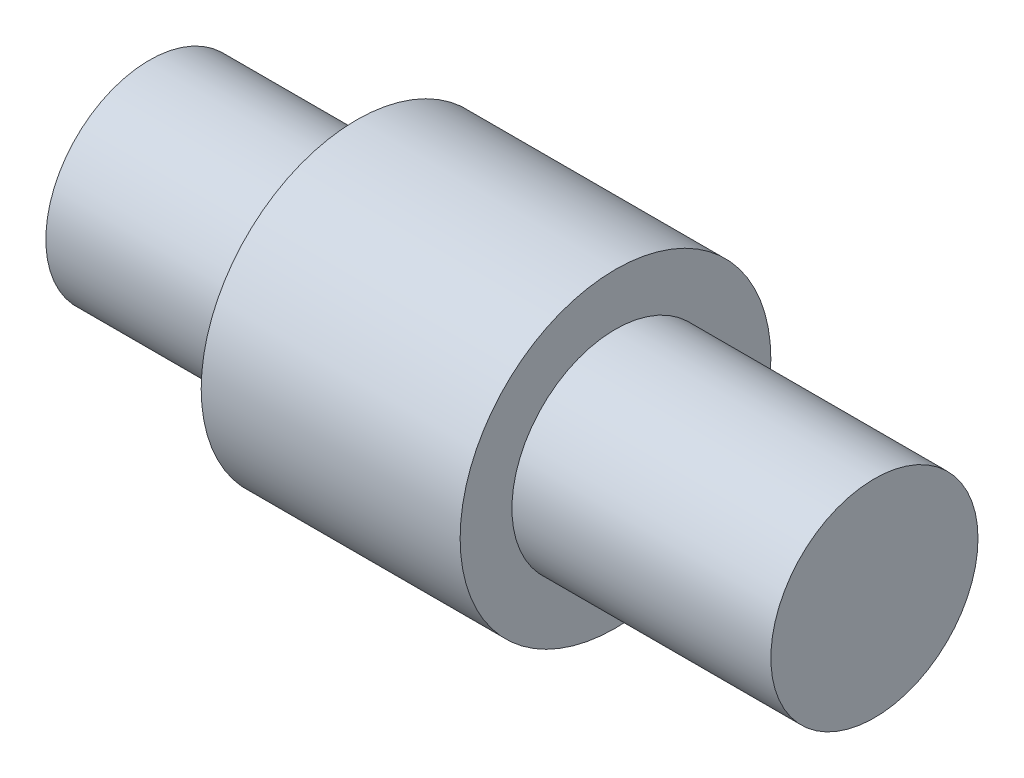
SolidWorks part; units mm, degrees
ref_plane "Front Plane" through (0, 0, 0) normal (0, 0, 1) x (1, 0, 0)
ref_plane "Top Plane" through (0, 0, 0) normal (0, 1, 0) x (1, 0, 0)
ref_plane "Right Plane" through (0, 0, 0) normal (1, 0, 0) x (0, 0, -1)
sketch "Sketch1" plane through (0, 0, 0) normal (1, 0, 0) x (0, 0, -1)
  circle A0 centre (0, 0) radius 3
  dimension "D1" = 6
extrude "Boss-Extrude1" add sketch "Sketch1" along normal blind 5
sketch "Sketch2" plane through (5, 0, 0) normal (1, 0, 0) x (0, 0, -1)
  circle A0 centre (0, 0) radius 2
  dimension "D1" = 4
extrude "Boss-Extrude2" add sketch "Sketch2" along normal blind 5 and the other way blind 9
